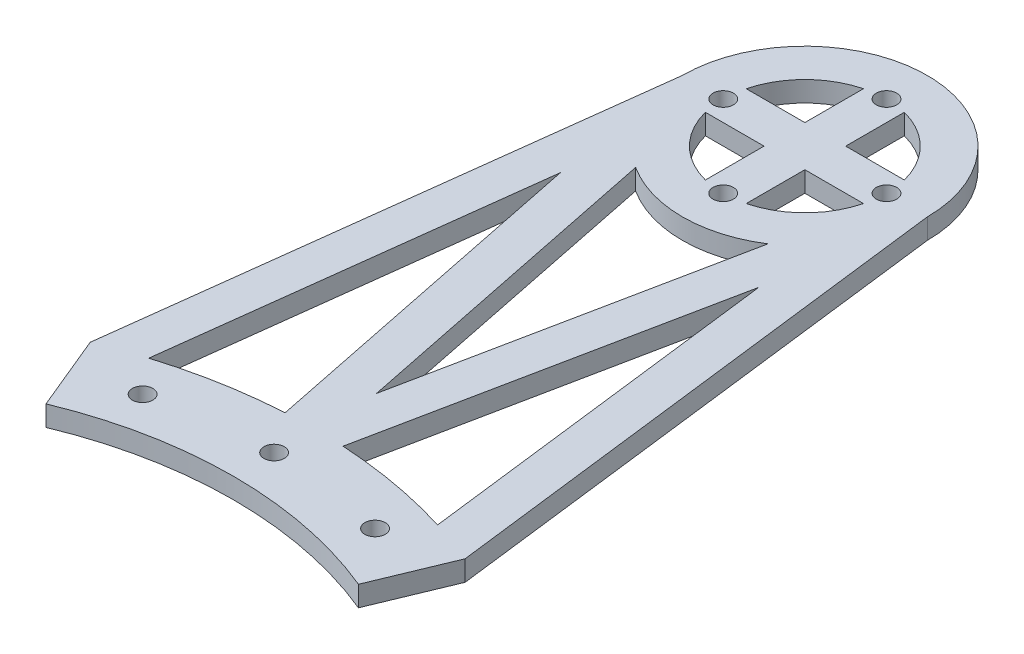
SolidWorks part; units mm, degrees
material "Acrylic (Medium-high impact)"
ref_plane "Front Plane" through (0, 0, 0) normal (0, 0, 1) x (1, 0, 0)
ref_plane "Top Plane" through (0, 0, 0) normal (0, 1, 0) x (1, 0, 0)
ref_plane "Right Plane" through (0, 0, 0) normal (1, 0, 0) x (0, 0, -1)
sketch "Sketch1" plane through (0, 0, 0) normal (0, 1, 0) x (1, 0, 0)
  line L0 (-19.05, 152.4) -> (-29.1605, 70.3996)
  line L2 (19.05, 152.4) -> (29.1605, 70.3996)
  line L4 (-15.4381, 129.8027) -> (-4.5049, 76.0667)
  line L6 (-10.2944, 136.371) -> (0, 85.7747)
  line L7 (-24.3004, 58.6664) -> (-29.1605, 70.3996)
  line L8 (0, 85.7747) -> (10.2944, 136.371)
  line L9 (24.3004, 58.6664) -> (29.1605, 70.3996)
  line L14 (12.2967, 155.575) -> (3.175, 155.575)
  line L15 (-16.2424, 149.225) -> (-26.0093, 70.0111) construction
  line L16 (-3.175, 149.225) -> (-12.2967, 149.225)
  line L17 (12.2967, 149.225) -> (3.175, 149.225)
  line L19 (21.8576, 155.575) -> (-21.8576, 155.575) construction
  line L20 (-21.8576, 155.575) -> (-32.3116, 70.7881) construction
  line L21 (21.8576, 155.575) -> (32.3116, 70.7881) construction
  line L23 (16.2424, 149.225) -> (26.0093, 70.0111) construction
  line L24 (4.5049, 76.0667) -> (15.4381, 129.8027)
  line L27 (19.05, 152.4) -> (-19.05, 152.4) construction
  line L28 (15.4381, 129.8027) -> (22.4648, 72.8133)
  line L29 (16.2424, 149.225) -> (-16.2424, 149.225) construction
  line L31 (3.175, 155.575) -> (3.175, 164.6967)
  line L33 (-3.175, 155.575) -> (-3.175, 164.6967)
  line L35 (-3.175, 155.575) -> (-12.2967, 155.575)
  line L36 (-15.4381, 129.8027) -> (-22.4648, 72.8133)
  line L37 (-3.175, 140.1033) -> (-3.175, 149.225)
  line L38 (3.175, 140.1033) -> (3.175, 149.225)
  arc A0 (19.05, 152.4) -> (-19.05, 152.4) centre (0, 152.4) ccw
  circle A1 centre (0, 139.7) radius 1.5875
  circle A2 centre (-12.7, 152.4) radius 1.5875
  circle A3 centre (0, 69.85) radius 1.5875
  circle A4 centre (18.0785, 67.4699) radius 1.5875
  circle A5 centre (0, 165.1) radius 1.5875
  circle A6 centre (12.7, 152.4) radius 1.5875
  arc A7 (12.2967, 155.575) -> (3.175, 164.6967) centre (0, 152.4) ccw
  arc A8 (-12.2967, 149.225) -> (-3.175, 140.1033) centre (0, 152.4) ccw
  arc A9 (3.175, 140.1033) -> (12.2967, 149.225) centre (0, 152.4) ccw
  arc A10 (22.4648, 72.8133) -> (4.5049, 76.0667) centre (0, 0) ccw
  arc A11 (-3.175, 164.6967) -> (-12.2967, 155.575) centre (0, 152.4) ccw
  arc A12 (-4.5049, 76.0667) -> (-22.4648, 72.8133) centre (0, 0) ccw
  circle A26 centre (-18.0785, 67.4699) radius 1.5875
  arc A31 (-10.2944, 136.371) -> (10.2944, 136.371) centre (0, 152.4) ccw
  arc A34 (24.3004, 58.6664) -> (-24.3004, 58.6664) centre (0, 0) ccw
  circle A35 centre (49.3914, 49.3914) radius 1.5875 [skipped]
  circle A36 centre (60.4919, 34.925) radius 1.5875 [skipped]
  circle A37 centre (67.4699, 18.0785) radius 1.5875 [skipped]
  circle A38 centre (69.85, 0) radius 1.5875 [skipped]
  circle A39 centre (67.4699, -18.0785) radius 1.5875 [skipped]
  circle A40 centre (60.4919, -34.925) radius 1.5875 [skipped]
  circle A41 centre (49.3914, -49.3914) radius 1.5875 [skipped]
  circle A42 centre (34.925, -60.4919) radius 1.5875 [skipped]
  circle A43 centre (18.0785, -67.4699) radius 1.5875 [skipped]
  circle A44 centre (0, -69.85) radius 1.5875 [skipped]
  circle A45 centre (-18.0785, -67.4699) radius 1.5875 [skipped]
  circle A46 centre (-34.925, -60.4919) radius 1.5875 [skipped]
  circle A47 centre (-49.3914, -49.3914) radius 1.5875 [skipped]
  circle A48 centre (-60.4919, -34.925) radius 1.5875 [skipped]
  circle A49 centre (-67.4699, -18.0785) radius 1.5875 [skipped]
  circle A50 centre (-69.85, 0) radius 1.5875 [skipped]
  circle A51 centre (-67.4699, 18.0785) radius 1.5875 [skipped]
  circle A52 centre (-60.4919, 34.925) radius 1.5875 [skipped]
  circle A53 centre (-49.3914, 49.3914) radius 1.5875 [skipped]
  circle A54 centre (-34.925, 60.4919) radius 1.5875 [skipped]
  circle A55 centre (34.925, 60.4919) radius 1.5875 [skipped]
  point P30 (0, 152.4)
  point P56 (0, 0)
  point P71 (0, 0)
extrude "Boss-Extrude1" add sketch "Sketch1" along normal blind 3.175
